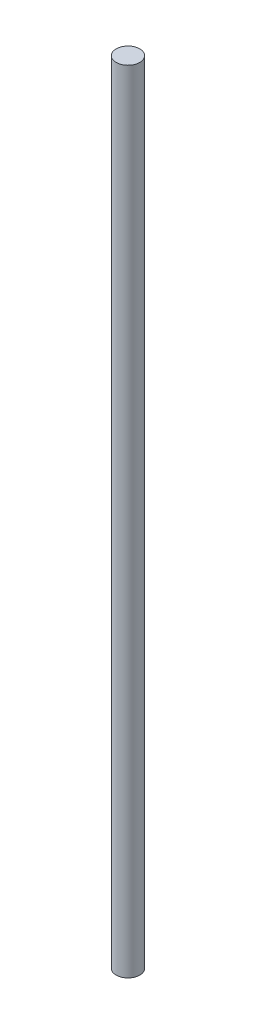
SolidWorks part; units mm, degrees
material "1060 合金"
ref_plane "前视基准面" through (0, 0, 0) normal (0, 0, 1) x (1, 0, 0)
ref_plane "上视基准面" through (0, 0, 0) normal (0, 1, 0) x (1, 0, 0)
ref_plane "右视基准面" through (0, 0, 0) normal (1, 0, 0) x (0, 0, -1)
other "Configuration Table"
sketch "草图1" plane through (0, 0, 0) normal (0, 1, 0) x (1, 0, 0)
  circle A0 centre (0, 0) radius 1
  dimension "D1" = 2
extrude "凸台-拉伸1" add sketch "草图1" along normal blind 67
